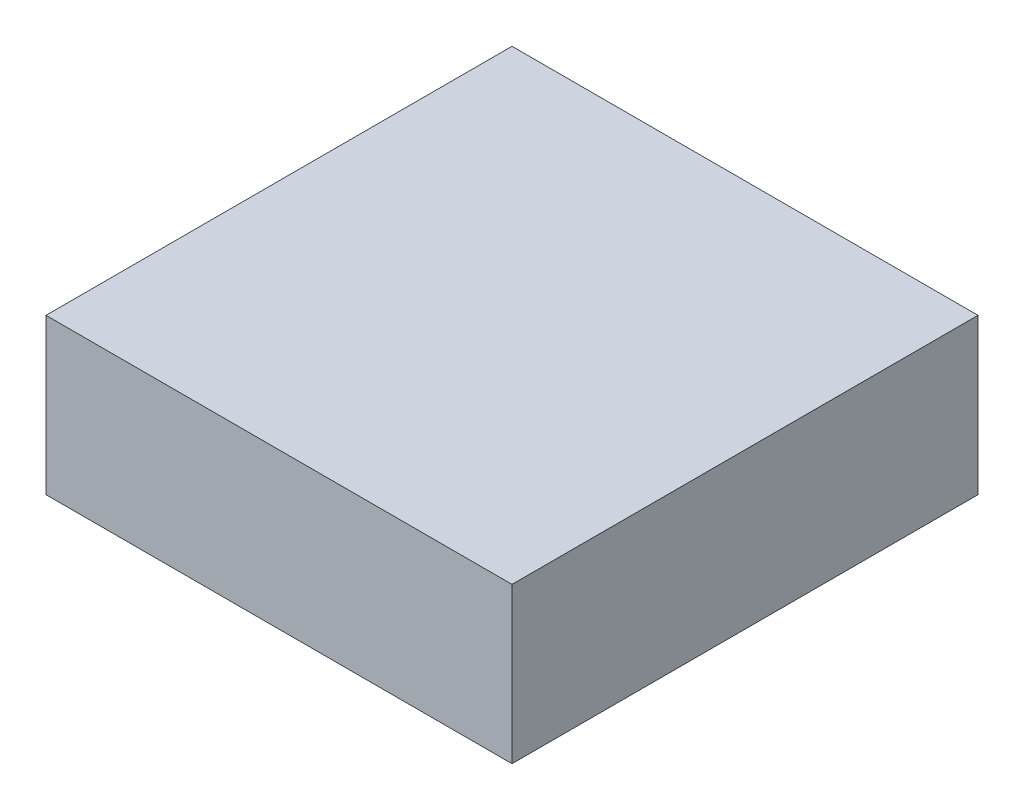
SolidWorks part; units mm, degrees
material "Кремний"
ref_plane "Front Plane" through (0, 0, 0) normal (0, 0, 1) x (1, 0, 0)
ref_plane "Top Plane" through (0, 0, 0) normal (0, 1, 0) x (1, 0, 0)
ref_plane "Right Plane" through (0, 0, 0) normal (1, 0, 0) x (0, 0, -1)
sketch "Эскиз1" plane through (0, 0, 0) normal (0, 1, 0) x (1, 0, 0)
  line L1 (0, 0) -> (150, 0)
  line L2 (0, 0) -> (0, 150)
  line L3 (0, 150) -> (150, 150)
  line L4 (150, 0) -> (150, 150)
  line L5 (47.424, 99.6059) -> (86.1236, 99.6059)
  line L6 (47.424, 99.6059) -> (47.424, 53.0068)
  line L7 (47.424, 53.0068) -> (86.1236, 53.0068)
  line L8 (86.1236, 99.6059) -> (86.1236, 53.0068)
  dimension "D1" = 150
  dimension "D2" = 150
extrude "Бобышка-Вытянуть1" add sketch "Эскиз1" along normal blind 50 contours L4 L3 L2 L1
